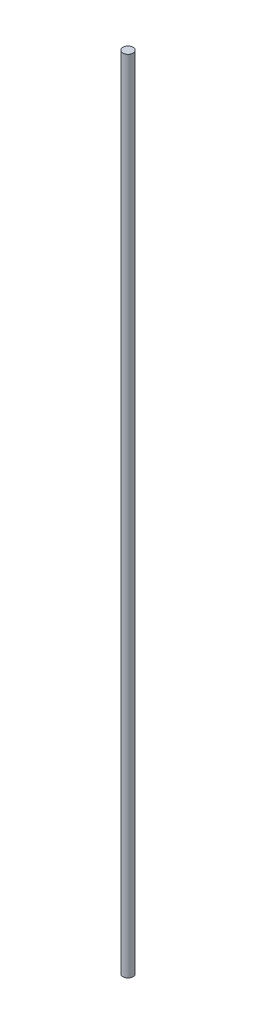
SolidWorks part; units mm, degrees
material "AISI 1020"
ref_plane "Front Plane" through (0, 0, 0) normal (0, 0, 1) x (1, 0, 0)
ref_plane "Top Plane" through (0, 0, 0) normal (0, 1, 0) x (1, 0, 0)
ref_plane "Right Plane" through (0, 0, 0) normal (1, 0, 0) x (0, 0, -1)
sketch "Sketch1" plane through (0, 0, 0) normal (0, 1, 0) x (1, 0, 0)
  circle A0 centre (0, 0) radius 1.6193
  dimension "D1" = 3.2385
extrude "Boss-Extrude1" add sketch "Sketch1" along normal blind 254
